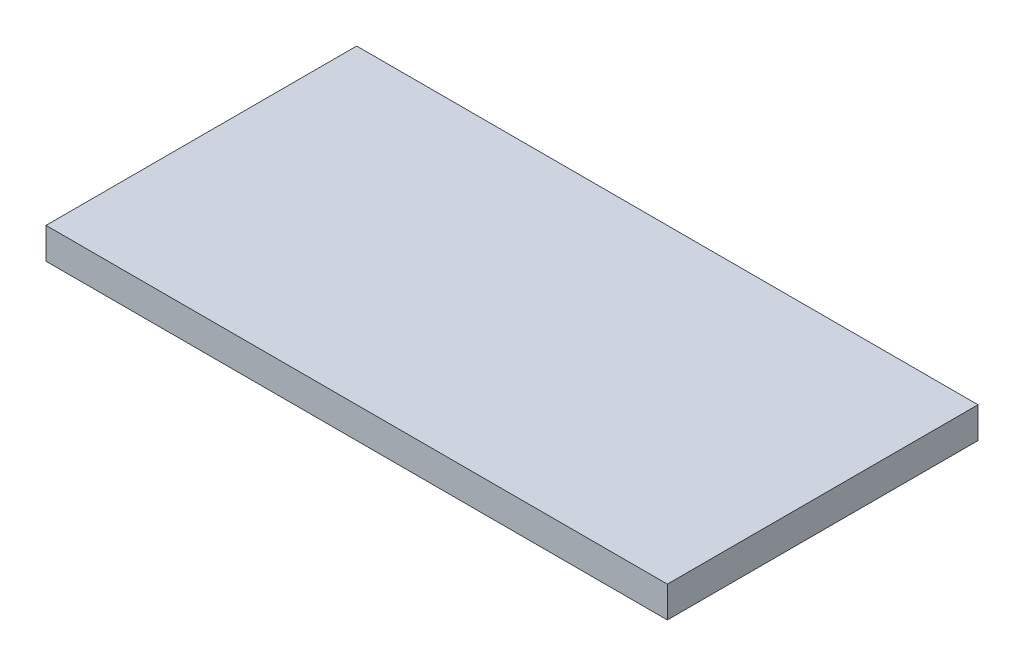
SolidWorks part; units mm, degrees
ref_plane "Front Plane" through (0, 0, 0) normal (0, 0, 1) x (1, 0, 0)
ref_plane "Top Plane" through (0, 0, 0) normal (0, 1, 0) x (1, 0, 0)
ref_plane "Right Plane" through (0, 0, 0) normal (1, 0, 0) x (0, 0, -1)
other "Configuration Table"
sketch "Sketch1" plane through (0, 0, 0) normal (0, 0, 1) x (1, 0, 0)
  line L1 (200, 862) -> (400, 862)
  line L2 (200, 862) -> (200, 872)
  line L3 (200, 872) -> (400, 872)
  line L4 (400, 862) -> (400, 872)
extrude "OVEN_sicak_dolap_isitici_100W_1" add sketch "Sketch1" against normal blind 100 from offset 300 separate body
